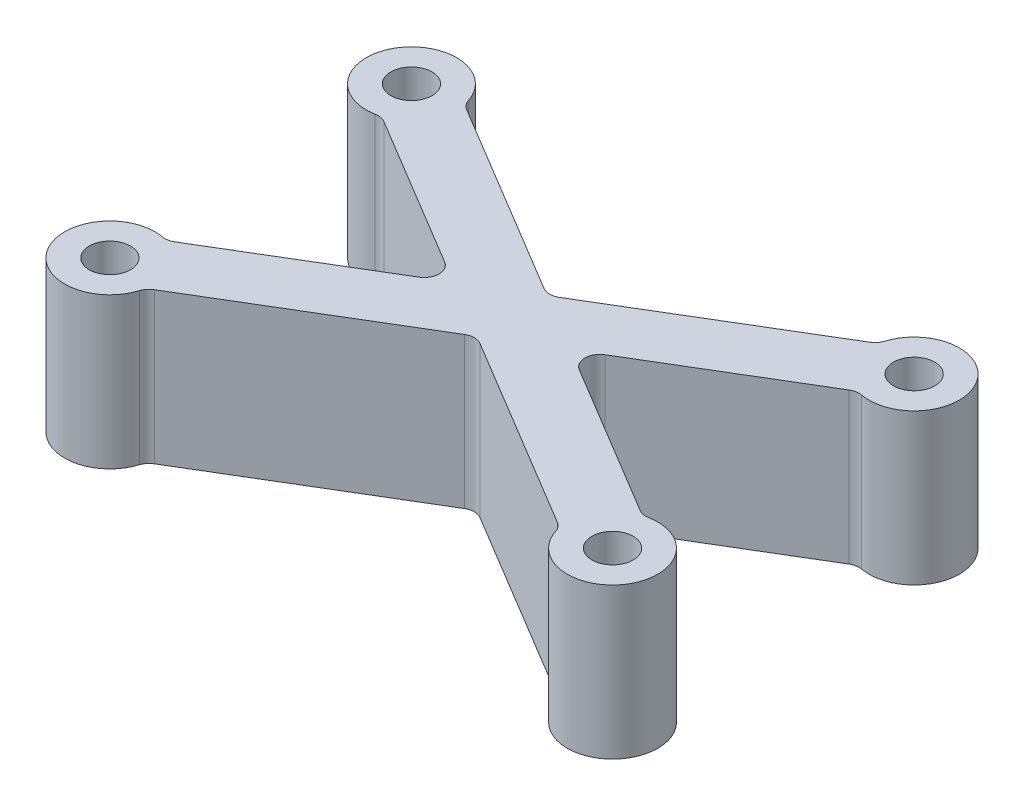
SolidWorks part; units mm, degrees
material "1060 合金"
ref_plane "前视基准面" through (0, 0, 0) normal (0, 0, 1) x (1, 0, 0)
ref_plane "上视基准面" through (0, 0, 0) normal (0, 1, 0) x (1, 0, 0)
ref_plane "右视基准面" through (0, 0, 0) normal (1, 0, 0) x (0, 0, -1)
sketch "草图1" plane through (0, 0, 0) normal (0, 1, 0) x (1, 0, 0)
  line L0 (-6, -6) -> (56, -6) construction
  line L1 (0, 0) -> (50, 0) construction
  line L2 (0, 0) -> (0, 30) construction
  line L3 (0, 30) -> (50, 30) construction
  line L4 (50, 0) -> (50, 30) construction
  line L9 (56, -6) -> (56, 36) construction
  line L10 (-6, 36) -> (56, 36) construction
  line L11 (-6, -6) -> (-6, 36) construction
  circle A0 centre (0, 0) radius 2.05
  circle A1 centre (0, 30) radius 2.05
  circle A2 centre (50, 30) radius 2.05
  circle A3 centre (50, 0) radius 2.05
  circle A4 centre (0, 0) radius 4.5
  circle A5 centre (0, 30) radius 4.5
  circle A6 centre (50, 30) radius 4.5
  circle A7 centre (50, 0) radius 4.5
  dimension "D7" = 4.1
  dimension "D3" = 9
  dimension "D1" = 30
  dimension "D2" = 50
  dimension "D8" = 6
extrude "凸台-拉伸1" add sketch "草图1" along normal blind 15
sketch "草图2" plane through (0, 15, 0) normal (0, 1, 0) x (1, 0, 0)
  line L0 (50, 0) -> (0, 30) construction
  line L1 (51.5435, 2.5725) -> (1.5435, 32.5725)
  line L2 (48.4565, -2.5725) -> (-1.5435, 27.4275)
  arc A0 (51.5435, 2.5725) -> (48.4565, -2.5725) centre (50, 0) cw
  arc A1 (1.5435, 32.5725) -> (-1.5435, 27.4275) centre (0, 30) ccw
  circle A2 centre (0, 30) radius 2.05
  circle A3 centre (50, 0) radius 2.05
  dimension "D1" = 3
  dimension "D2" = 3
extrude "凸台-拉伸2" add sketch "草图2" against normal up to surface (15 mm away) up to face at (50, 0, 4.5)
sketch "草图3" plane through (0, 15, 0) normal (0, 1, 0) x (1, 0, 0)
  line L0 (0, 0) -> (50, 30) construction
  line L1 (-1.5435, 2.5725) -> (48.4565, 32.5725)
  line L2 (1.5435, -2.5725) -> (51.5435, 27.4275)
  arc A0 (-1.5435, 2.5725) -> (1.5435, -2.5725) centre (0, 0) ccw
  arc A1 (51.5435, 27.4275) -> (48.4565, 32.5725) centre (50, 30) ccw
  circle A2 centre (0, 0) radius 2.05
  circle A3 centre (50, 30) radius 2.05
  point P4 (25, 15)
  dimension "D1" = 3
extrude "凸台-拉伸3" add sketch "草图3" against normal up to surface (15 mm away) up to face at (25, 0, -15)
fillet "圆角1" radius 1.5 12 edges at (45.5804, 7.5, -30.8468) (48.6674, 7.5, -4.2982) (48.6674, 7.5, -25.7018) (45.5804, 7.5, 0.8468) (25, 7.5, -11.5014) (30.831, 7.5, -15) (25, 7.5, -18.4986) (19.169, 7.5, -15) (1.3326, 7.5, -25.7018) (4.4196, 7.5, -30.8468) (1.3326, 7.5, -4.2982) (4.4196, 7.5, 0.8468)
